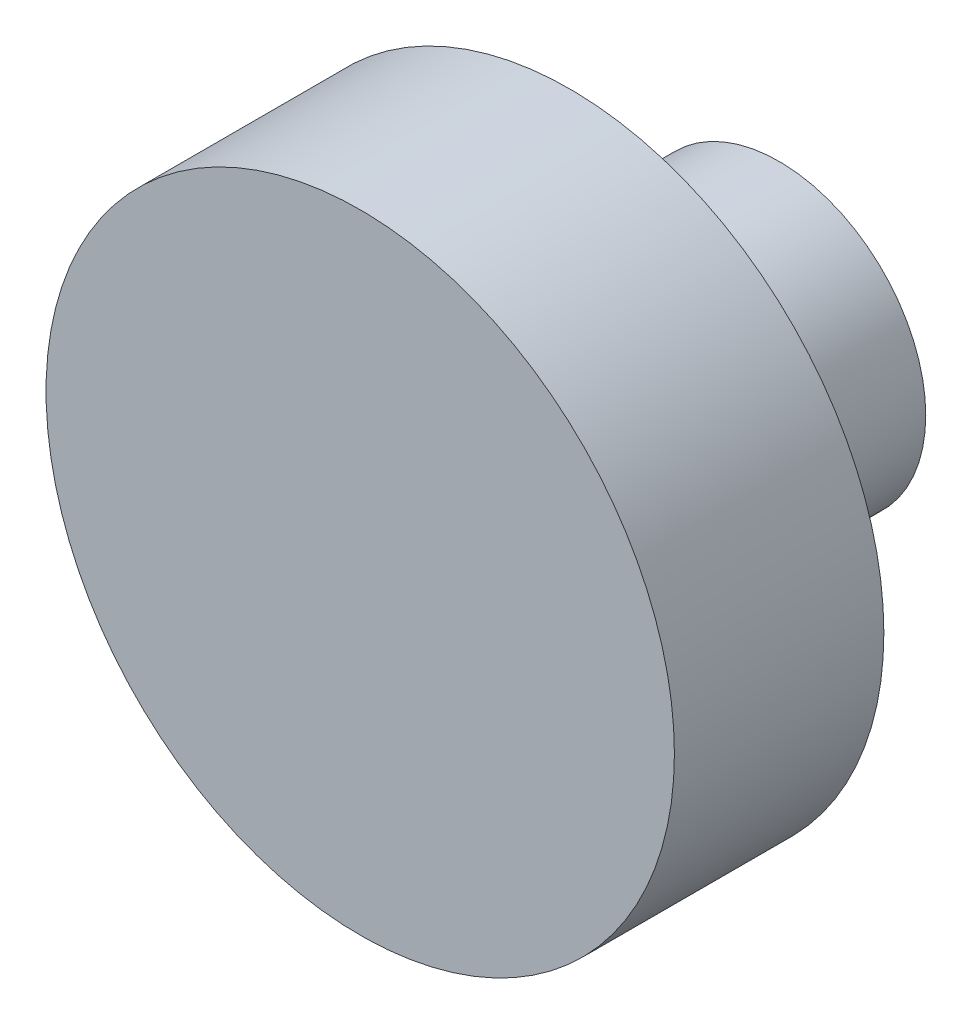
SolidWorks part; units mm, degrees
material "Латунь"
ref_plane "Спереди" through (0, 0, 0) normal (0, 0, 1) x (1, 0, 0)
ref_plane "Сверху" through (0, 0, 0) normal (0, 1, 0) x (1, 0, 0)
ref_plane "Справа" through (0, 0, 0) normal (1, 0, 0) x (0, 0, -1)
sketch "Эскиз1" plane through (0, 0, 0) normal (0, 0, 1) x (1, 0, 0)
  circle A0 centre (0, 0) radius 1.4
  dimension "D1" = 2.8
extrude "Бобышка-Вытянуть1" add sketch "Эскиз1" along normal blind 2
sketch "Эскиз2" plane through (0, 0, 2) normal (0, 0, 1) x (1, 0, 0)
  circle A0 centre (0, 0) radius 3
  dimension "D1" = 6
extrude "Бобышка-Вытянуть2" add sketch "Эскиз2" along normal blind 2
